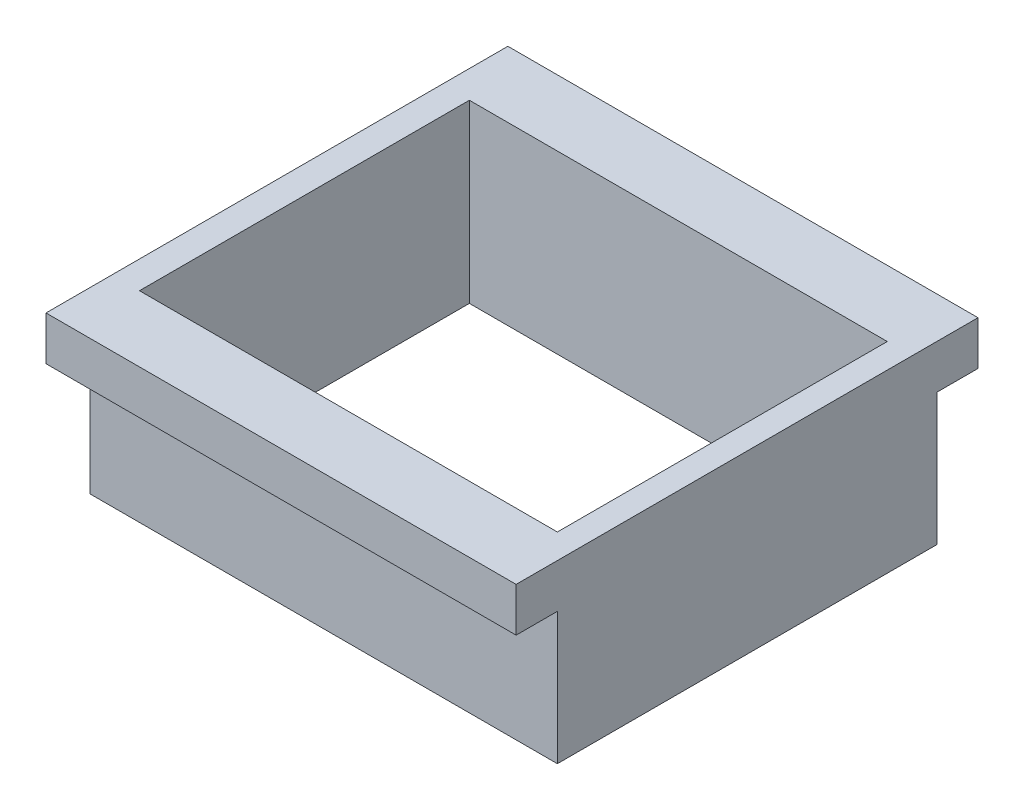
SolidWorks part; units mm, degrees
ref_plane "Спереди" through (0, 0, 0) normal (0, 0, 1) x (1, 0, 0)
ref_plane "Сверху" through (0, 0, 0) normal (0, 1, 0) x (1, 0, 0)
ref_plane "Справа" through (0, 0, 0) normal (1, 0, 0) x (0, 0, -1)
sketch "Эскиз1" plane through (0, 0, 0) normal (0, 1, 0) x (1, 0, 0)
  line L0 (21.25, -17.25) -> (-21.25, -17.25)
  line L1 (-21.25, -17.25) -> (-21.25, 17.25)
  line L3 (21.25, 17.25) -> (21.25, -17.25)
  line L5 (-21.25, 17.25) -> (21.25, 17.25)
  line L6 (-19, 15) -> (19, 15)
  line L8 (-19, 15) -> (-19, -15)
  line L9 (-19, -15) -> (19, -15)
  line L10 (19, -15) -> (19, 15)
  point P0 (0, 0)
extrude "Бобышка-Вытянуть1" add sketch "Эскиз1" along normal blind 12
ref_plane "Плоскость1" through (0, 12, 0) normal (0, 1, 0) x (1, 0, 0)
sketch "Эскиз2" plane through (0, 12, 0) normal (0, 1, 0) x (1, 0, 0)
  line L0 (-21.5, -21) -> (-21.5, 21)
  line L1 (-21.5, 21) -> (21.25, 21)
  line L2 (21.25, 21) -> (21.25, -21)
  line L3 (21.25, -21) -> (-21.5, -21)
  line L4 (-19, 15) -> (-19, -15)
  line L5 (-19, -15) -> (19, -15)
  line L6 (19, -15) -> (19, 15)
  line L7 (19, 15) -> (-19, 15)
  point P8 (0, 0)
extrude "Бобышка-Вытянуть2" add sketch "Эскиз2" along normal blind 4
